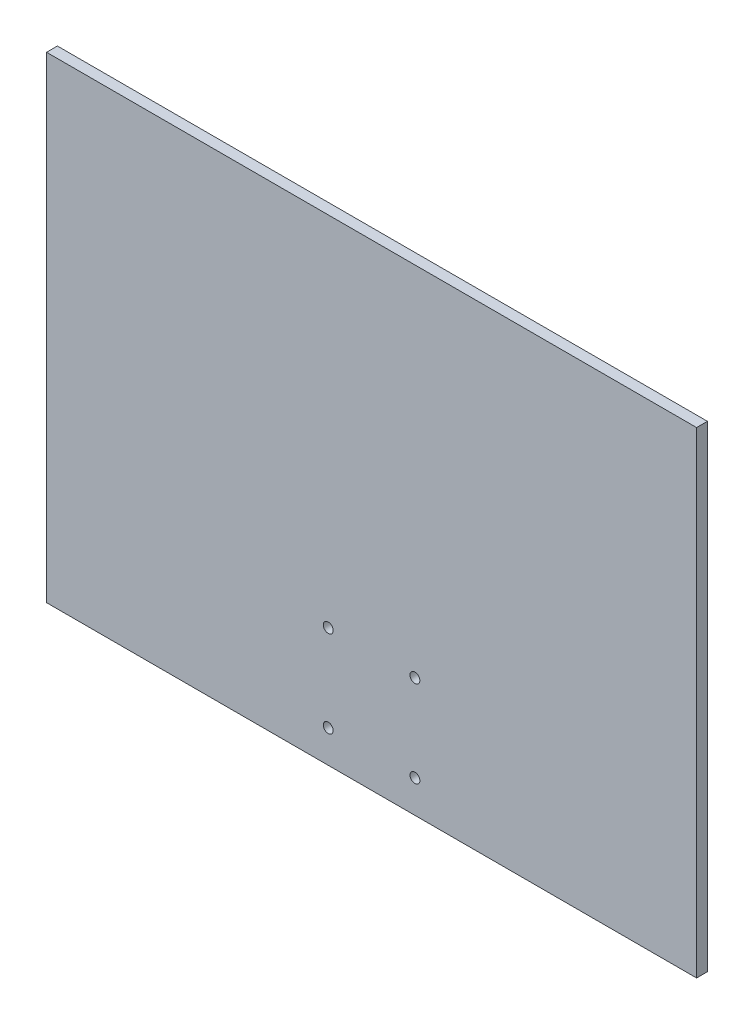
SolidWorks part; units mm, degrees
material "Pine"
ref_plane "Front Plane" through (0, 0, 0) normal (0, 0, 1) x (1, 0, 0)
ref_plane "Top Plane" through (0, 0, 0) normal (0, 1, 0) x (1, 0, 0)
ref_plane "Right Plane" through (0, 0, 0) normal (1, 0, 0) x (0, 0, -1)
sketch "Sketch1" plane through (0, 0, 0) normal (0, 0, 1) x (1, 0, 0)
  line L1 (-190.5, -139.7) -> (190.5, -139.7)
  line L2 (-190.5, -139.7) -> (-190.5, 139.7)
  line L3 (-190.5, 139.7) -> (190.5, 139.7)
  line L4 (190.5, -139.7) -> (190.5, 139.7)
  line L5 (-190.5, -139.7) -> (190.5, 139.7) construction
  line L6 (-190.5, 139.7) -> (190.5, -139.7) construction
  point P0 (0, 0)
  dimension "D1" = 279.4
  dimension "D2" = 381
extrude "Boss-Extrude1" add sketch "Sketch1" along normal blind 6.35
hole_wizard "M5 Clearance Hole1" positions "Sketch3" profile "Sketch4" hole size "M5" standard "ANSI Metric"
sketch "Sketch3" plane through (0, 0, 6.35) normal (0, 0, 1) x (1, 0, 0)
  line L0 (0, 139.7) -> (0, -139.7) construction
  line L1 (190.5, 139.7) -> (-190.5, 139.7) construction
  line L2 (-190.5, -139.7) -> (190.5, -139.7) construction
  line L4 (25.4, -120.65) -> (-25.4, -120.65)
  line L5 (25.4, -120.65) -> (25.4, -69.85)
  line L6 (25.4, -69.85) -> (-25.4, -69.85)
  line L7 (-25.4, -120.65) -> (-25.4, -69.85)
  line L8 (25.4, -120.65) -> (-25.4, -69.85) construction
  line L9 (25.4, -69.85) -> (-25.4, -120.65) construction
  point P25 (0, -95.25)
  point P26 (-25.4, -69.85)
  point P161 (25.4, -120.65)
  point P162 (25.4, -69.85)
  point P163 (-25.4, -120.65)
  dimension "D1" = 50.8
  dimension "D2" = 50.8
  dimension "D3" = 19.05
sketch "Sketch4" plane through (-25.4, -120.65, 6.35) normal (1, 0, 0) x (0, -1, 0)
  line L0 (0, 0) -> (0, 6.35)
  line L1 (0, 6.35) -> (2.9, 6.35)
  line L2 (2.9, 6.35) -> (2.9, 0)
  line L5 (2.9, 0) -> (0, 0)
  line L11 (0, -6.35) -> (0, 107.95) construction
  dimension "Thru Hole Dia." = 5.8
  dimension "Thru Hole Depth" = 6.35
